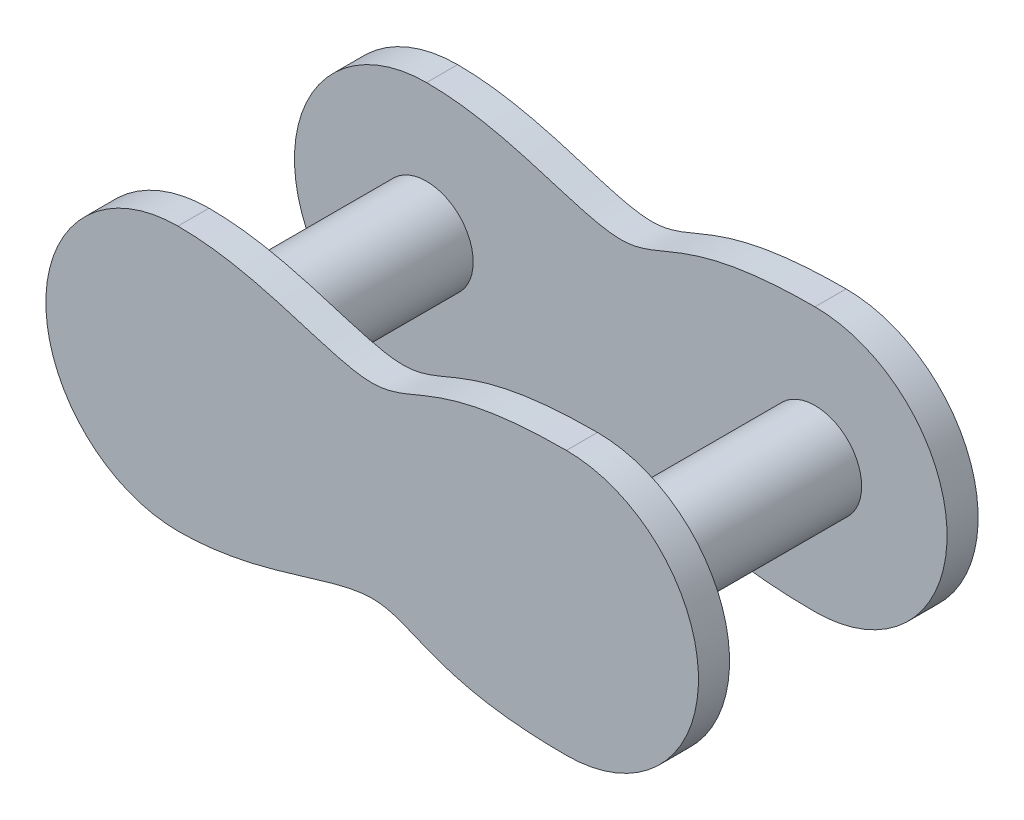
SolidWorks part; units mm, degrees
ref_plane "Front Plane" through (0, 0, 0) normal (0, 0, 1) x (1, 0, 0)
ref_plane "Top Plane" through (0, 0, 0) normal (0, 1, 0) x (1, 0, 0)
ref_plane "Right Plane" through (0, 0, 0) normal (1, 0, 0) x (0, 0, -1)
sketch "Sketch1" plane through (0, 0, 0) normal (0, 0, 1) x (1, 0, 0)
  circle A0 centre (0, 0) radius 1.5
  circle A1 centre (12.5, 0) radius 1.5
  dimension "D1" = 3
  dimension "D2" = 3
  dimension "D3" = 12.5
extrude "Boss-Extrude1" add sketch "Sketch1" along normal blind 7
sketch "Sketch2" plane through (0, 0, 7) normal (0, 0, 1) x (1, 0, 0)
  line L0 (-5.9471, 0) -> (17.7122, 0) construction
  line L1 (0, 5.4423) -> (0, -5.4248) construction
  line L2 (12.5, 5.4423) -> (12.5, -6.5973) construction
  arc A0 (0, 4.25) -> (0, -4.25) centre (0, 0) ccw
  arc A1 (12.5, -4.25) -> (12.5, 4.25) centre (12.5, 0) ccw
  spline S0 degree 3 poles (0, 4.25) (2.674, 4.25) (7.0639, 1.75) (8.1982, 4.25) (12.5, 4.25) knots 0 0 0 0 0.5 1 1 1 1
  spline S1 degree 3 poles (0, -4.25) (2.674, -4.25) (7.0639, -1.75) (8.1982, -4.25) (12.5, -4.25) knots 0 0 0 0 0.5 1 1 1 1
  dimension "D1" = 8.5
  dimension "D2" = 8.5
  dimension "D3" = 1.25
  dimension "D4" = 6.25
extrude "Boss-Extrude2" add sketch "Sketch2" along normal blind 1
sketch "Sketch3" plane through (0, 0, 0) normal (0, 0, -1) x (-1, 0, 0)
  arc A2 (0, -4.25) -> (0, 4.25) centre (0, 0) ccw construction
  arc A3 (-12.5, 4.25) -> (-12.5, -4.25) centre (-12.5, 0) ccw construction
  arc A6 (0, -4.25) -> (0, 4.25) centre (0, 0) ccw
  arc A7 (-12.5, 4.25) -> (-12.5, -4.25) centre (-12.5, 0) ccw
  spline S0 degree 3 poles (-46.5134, 1993.7656) (99.0977, -123.199) (-62.9832, 89.0111) (18.8764, -73.4335) (-1823.6367, 843.1107) knots -4.40304 -4.40304 -4.40304 -4.40304 0.5 4.253225 4.253225 4.253225 4.253225 only from (0, -4.25) to (-12.5, -4.25) construction
  spline S1 degree 3 poles (-1823.6505, -843.1176) (18.8765, 73.4339) (-62.9835, -89.0115) (99.0981, 123.1995) (-46.5143, -1993.779) knots -3.253235 -3.253235 -3.253235 -3.253235 0.5 5.403051 5.403051 5.403051 5.403051 only from (-12.5, 4.25) to (0, 4.25) construction
  spline S2 degree 3 poles (0, -4.25) (-2.674, -4.25) (-7.0639, -1.75) (-8.1982, -4.25) (-12.5, -4.25) knots 0 0 0 0 0.5 1 1 1 1
  spline S3 degree 3 poles (-12.5, 4.25) (-8.1982, 4.25) (-7.0639, 1.75) (-2.674, 4.25) (0, 4.25) knots 0 0 0 0 0.5 1 1 1 1
extrude "Boss-Extrude3" add sketch "Sketch3" along normal blind 1 separate body
ref_plane "Plane1" through (0, 0, 3.5) normal (0, 0, 1) x (1, 0, 0)
